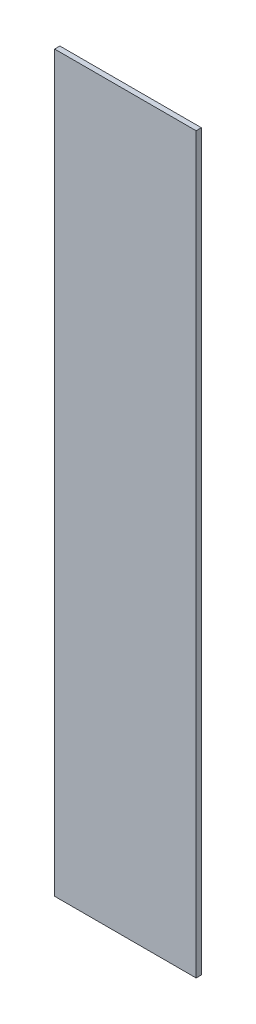
SolidWorks part; units mm, degrees
ref_plane "Front" through (0, 0, 0) normal (0, 0, 1) x (1, 0, 0)
ref_plane "Top" through (0, 0, 0) normal (0, 1, 0) x (1, 0, 0)
ref_plane "Right" through (0, 0, 0) normal (1, 0, 0) x (0, 0, -1)
sketch "Sketch1" plane through (0, 0, 0) normal (0, 0, 1) x (1, 0, 0)
  line L5 (-171.45, -889) -> (171.45, -889)
  line L6 (-171.45, -889) -> (-171.45, 889)
  line L7 (-171.45, 889) -> (171.45, 889)
  line L8 (171.45, -889) -> (171.45, 889)
  line L9 (-171.45, -889) -> (171.45, 889) construction
  line L10 (-171.45, 889) -> (171.45, -889) construction
  point P4 (0, 0)
  dimension "D1" = 342.9
  dimension "D2" = 1778
extrude "Boss-Extrude1" add sketch "Sketch1" along normal blind 12.7
